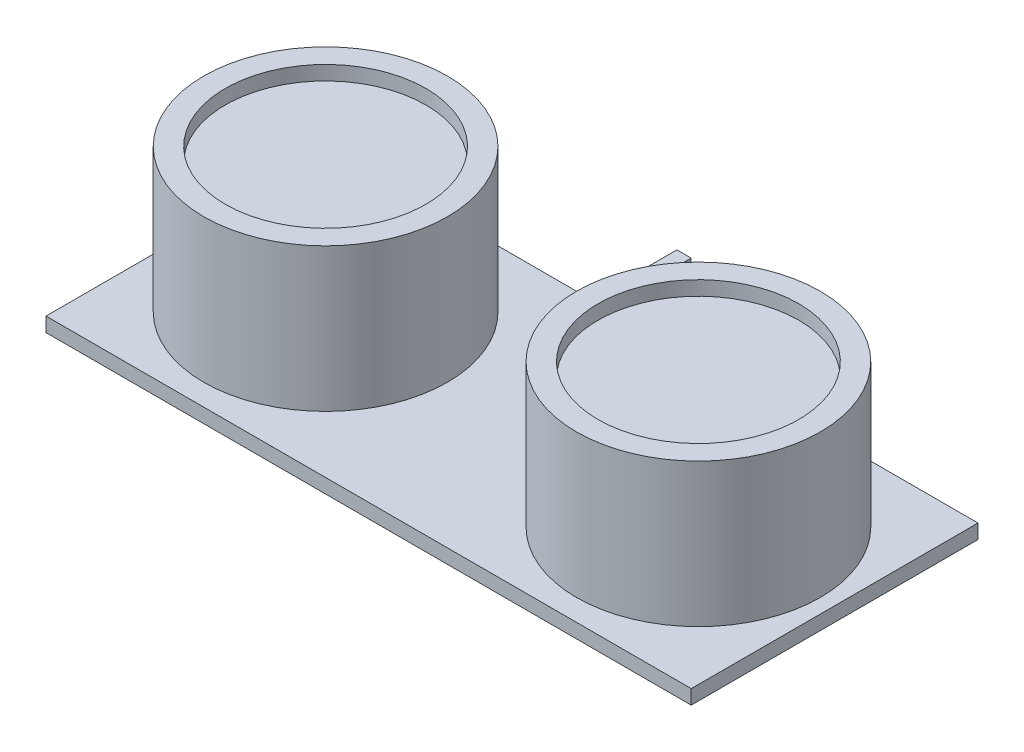
SolidWorks part; units mm, degrees
ref_plane "Front Plane" through (0, 0, 0) normal (0, 0, 1) x (1, 0, 0)
ref_plane "Top Plane" through (0, 0, 0) normal (0, 1, 0) x (1, 0, 0)
ref_plane "Right Plane" through (0, 0, 0) normal (1, 0, 0) x (0, 0, -1)
sketch "Sketch1" plane through (0, 0, 0) normal (0, 1, 0) x (1, 0, 0)
  line L1 (-22.5, 10) -> (22.5, 10)
  line L2 (-22.5, 10) -> (-22.5, -10)
  line L3 (-22.5, -10) -> (22.5, -10)
  line L4 (22.5, 10) -> (22.5, -10)
  dimension "D1" = 45
  dimension "D2" = 20
  dimension "D3" = 22.5
  dimension "D4" = 10
extrude "Boss-Extrude1" add sketch "Sketch1" along normal blind 1
sketch "Sketch2" plane through (0, 1, 0) normal (0, 1, 0) x (1, 0, 0)
  circle A0 centre (-13, 0) radius 8.5
  circle A1 centre (13, 0) radius 8.5
  dimension "D1" = 17
  dimension "D2" = 17
  dimension "D3" = 13
  dimension "D4" = 13
extrude "Boss-Extrude2" add sketch "Sketch2" along normal blind 10
sketch "Sketch3" plane through (0, 11, 0) normal (0, 1, 0) x (1, 0, 0)
  circle A0 centre (-13, 0) radius 7
  circle A1 centre (13, 0) radius 7
  circle A2 centre (-13, 0) radius 8.5 construction
  circle A3 centre (13, 0) radius 8.5 construction
  dimension "D1" = 14
  dimension "D2" = 14
extrude "Cut-Extrude1" cut sketch "Sketch3" against normal blind 1
sketch "Sketch4" plane through (0, 1, 0) normal (0, 1, 0) x (1, 0, 0)
  line L0 (-1.5, 15) -> (-0.5, 15)
  line L1 (-3.5, 8) -> (-2.5, 8)
  line L2 (-3.5, 8) -> (-3.5, 15)
  line L3 (-3.5, 15) -> (-2.5, 15)
  line L4 (3.5, 8) -> (3.5, 15)
  line L5 (-1.5, 8) -> (-0.5, 8)
  line L6 (-2.5, 15) -> (-2.5, 8)
  line L7 (0.5, 8) -> (1.5, 8)
  line L8 (-1.5, 15) -> (-1.5, 8)
  line L9 (2.5, 15) -> (3.5, 15)
  line L10 (-0.5, 15) -> (-0.5, 8)
  line L11 (2.5, 8) -> (3.5, 8)
  line L12 (0.5, 15) -> (0.5, 8)
  line L14 (1.5, 15) -> (1.5, 8)
  line L16 (2.5, 15) -> (2.5, 8)
  line L17 (0.5, 15) -> (1.5, 15)
  point P16 (0, 0)
  dimension "D1" = 1
  dimension "D2" = 1
  dimension "D3" = 1
  dimension "D4" = 1
  dimension "D5" = 1
  dimension "D6" = 1
  dimension "D7" = 1
  dimension "D8" = 3.5
  dimension "D9" = 8
  dimension "D10" = 15
extrude "Boss-Extrude3" add sketch "Sketch4" along normal blind 1
